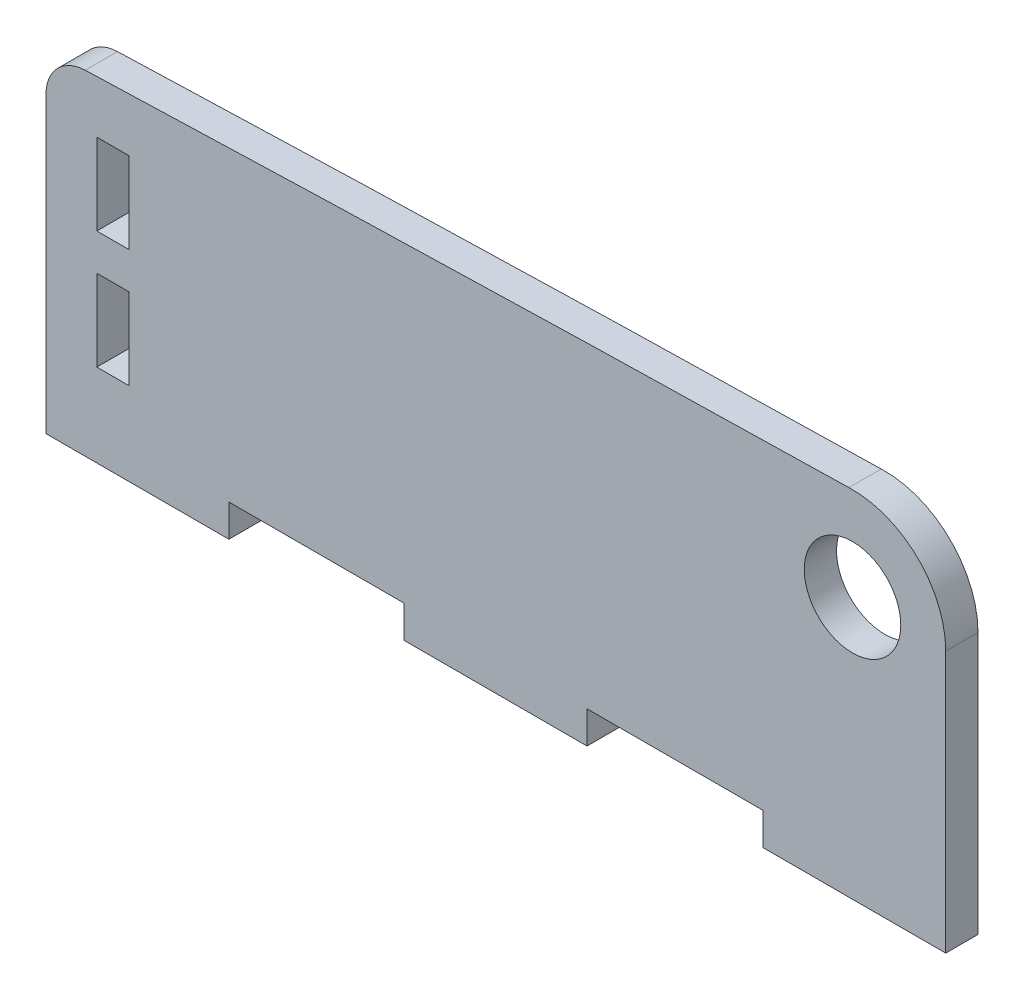
SolidWorks part; units mm, degrees
ref_plane "Front Plane" through (0, 0, 0) normal (0, 0, 1) x (1, 0, 0)
ref_plane "Top Plane" through (0, 0, 0) normal (0, 1, 0) x (1, 0, 0)
ref_plane "Right Plane" through (0, 0, 0) normal (1, 0, 0) x (0, 0, -1)
sketch "Sketch1" plane through (0, 0, 0) normal (0, 0, 1) x (1, 0, 0)
  line L1 (-26.416, -9.8) -> (26.416, -9.8)
  line L2 (-26.416, -9.8) -> (-26.416, 9.8)
  line L3 (-26.416, 9.8) -> (26.416, 9.8)
  line L4 (26.416, -9.8) -> (26.416, 9.8)
  line L5 (-26.416, -9.8) -> (26.416, 9.8) construction
  line L6 (-26.416, 9.8) -> (26.416, -9.8) construction
  line L7 (-20.15, -9.8) -> (20.15, -9.8)
  line L8 (-20.15, -9.8) -> (-20.15, 9.8)
  line L9 (-20.15, 9.8) -> (20.15, 9.8)
  line L10 (20.15, -9.8) -> (20.15, 9.8)
  line L11 (-20.15, -9.8) -> (20.15, 9.8) construction
  line L12 (-20.15, 9.8) -> (20.15, -9.8) construction
  line L13 (-26.416, 9.8) -> (26.416, 9.8)
  line L14 (-26.416, 9.8) -> (-26.416, 14.8)
  line L15 (-26.416, 14.8) -> (26.416, 14.8)
  line L16 (26.416, 9.8) -> (26.416, 14.8)
  line L17 (26.416, -9.8) -> (-26.416, -9.8)
  line L18 (26.416, -9.8) -> (26.416, -14.8)
  line L19 (26.416, -14.8) -> (-26.416, -14.8)
  line L20 (-26.416, -9.8) -> (-26.416, -14.8)
  circle A0 centre (-23.95, -4.974) radius 1.675
  circle A1 centre (-23.95, 4.974) radius 1.675
  circle A2 centre (23.95, 4.974) radius 1.675
  circle A3 centre (23.95, -4.974) radius 1.675
  point P0 (0, 0)
  point P14 (0, 0)
  dimension "D1" = 3.35
  dimension "D2" = 3.35
  dimension "D3" = 3.35
  dimension "D4" = 3.35
  dimension "D7" = 4.826
  dimension "D8" = 3.8
  dimension "D9" = 3.8
  dimension "D10" = 4.826
  dimension "D11" = 4.826
  dimension "D12" = 4.826
  dimension "D13" = 3.8
  dimension "D5" = 19.6
  dimension "D6" = 52.832
  dimension "D15" = 40.3
  dimension "D16" = 5
  dimension "D17" = 5
  dimension "3.9" = 3.8
extrude "Boss-Extrude2" add sketch "Sketch1" along normal blind 3.175 contours L1 L8 L3 L2 A1 A0 | L10 L1 L4 L3 A3 A2 | L14 L13 L16 L15 | L18 L17 L20 L19
sketch "Sketch3" plane through (0, 0, 3.175) normal (0, 0, 1) x (1, 0, 0)
  line L0 (26.416, -14.8) -> (56.416, -14.8)
  line L6 (26.416, 14.8) -> (56.416, 14.8)
  line L7 (26.416, 14.8) -> (26.416, -14.906)
  line L8 (26.416, -14.906) -> (56.416, -14.906)
  line L9 (56.416, 14.8) -> (56.416, -14.906)
  line M3 (26.416, -14.8) -> (26.416, 14.8)
  dimension "D2" = 30
extrude "Boss-Extrude3" add sketch "Sketch3" against normal up to surface (3.175 mm away) contours L9 L6 L0 M3 up to face at (0, 0, 0)
sketch "Sketch4" plane through (0, 0, 0) normal (0, 0, -1) x (-1, 0, 0)
  line L3 (-56.416, 14.8) -> (-56.416, -14.8) construction
  line L4 (-56.416, -14.8) -> (26.416, -14.8) construction
  circle A0 centre (-40.576, 7.77) radius 4.75
  dimension "D1" = 15.84
  dimension "D2" = 22.57
  dimension "D3" = 9.5
extrude "Cut-Extrude1" cut sketch "Sketch4" against normal blind 10 contours A0
sketch "Sketch22" plane through (0, 0, 0) normal (0, 0, -1) x (-1, 0, 0)
  line L0 (-52.3294, 14.8) -> (-30.0917, 14.8)
  line L1 (26.416, 14.8) -> (-56.416, 14.8) construction
  circle A0 centre (-40.576, 7.77) radius 9.175
  dimension "D1" = 18.35
extrude "Boss-Extrude14" add sketch "Sketch22" against normal up to surface (3.175 mm away) contours L0 A0
sketch "Sketch23" plane through (0, 0, 0) normal (0, 0, -1) x (-1, 0, 0)
  line L0 (-49.751, 7.77) -> (-49.751, -14.8)
  line L1 (-56.416, -14.8) -> (26.416, -14.8) construction
  circle A0 centre (-40.576, 7.77) radius 9.175
  line M4 (-46.4717, 14.8) -> (-56.416, 14.8)
  line M5 (-56.416, 14.8) -> (-56.416, -14.8)
  line M6 (-56.416, -14.8) -> (26.416, -14.8)
extrude "Cut-Extrude8" cut sketch "Sketch23" against normal blind 10 contours A0 L0 M4 M5 M6
sketch "Sketch24" plane through (0, 0, 0) normal (0, 0, -1) x (-1, 0, 0)
  line L0 (25.625, 4.974) -> (25.625, 17.1862)
  line L1 (21.4452, -14.8) -> (27.751, -14.8)
  line L2 (-49.751, -14.8) -> (26.416, -14.8) construction
  line L3 (26.416, 14.8) -> (-34.6803, 14.8) construction
  line L4 (25.625, 14.8) -> (30.625, 14.8)
  line L5 (25.625, 14.8) -> (25.625, -14.8)
  line L6 (25.625, -14.8) -> (30.625, -14.8)
  line L7 (30.625, 14.8) -> (30.625, -14.8)
  circle A0 centre (23.95, 4.974) radius 1.675 construction
  line M14 (26.416, -14.8) -> (26.416, 14.8)
  dimension "D1" = 5
extrude "Boss-Extrude15" add sketch "Sketch24" against normal up to surface (3.175 mm away) contours L7 L4 L1 L6 M14 up to face at (45.326, 7.77, 3.175)
sketch "Sketch25" plane through (0, 0, 0) normal (0, 0, -1) x (-1, 0, 0)
  line L0 (30.625, 14.8) -> (30.625, -14.8) construction
  line L1 (30.625, 9.8) -> (33.8, 9.8)
  line L2 (30.625, 9.8) -> (30.625, 1.8)
  line L3 (30.625, 1.8) -> (33.8, 1.8)
  line L4 (33.8, 9.8) -> (33.8, 1.8)
  line L5 (28.9462, -14.8) -> (31.8791, -14.8)
  line L6 (30.625, -1.8) -> (33.8, -1.8)
  line L7 (30.625, -1.8) -> (30.625, -9.8)
  line L8 (30.625, -9.8) -> (33.8, -9.8)
  line L9 (33.8, -1.8) -> (33.8, -9.8)
  line L10 (-49.751, -14.8) -> (30.625, -14.8) construction
  line L12 (30.625, 14.8) -> (38.8, 14.8)
  line L13 (30.625, 14.8) -> (30.625, -14.8)
  line L14 (30.625, -14.8) -> (38.8, -14.8)
  line L15 (38.8, 14.8) -> (38.8, -14.8)
  line M23 (30.625, -14.8) -> (30.625, 14.8)
  dimension "D1" = 3.175
  dimension "D2" = 3.175
  dimension "D3" = 8
  dimension "D4" = 8
  dimension "D5" = 5
  dimension "D6" = 0
  dimension "D7" = 8.175
  dimension "D8" = 5
extrude "Boss-Extrude16" add sketch "Sketch25" against normal up to surface (3.175 mm away) contours L15 L12 L1 L4 L3 L6 L9 L8 L5 L14 M23 up to face at (45.326, 7.77, 3.175)
sketch "Sketch26" plane through (0, 0, 0) normal (0, 0, -1) x (-1, 0, 0)
  line L0 (-34.6803, 14.8) -> (38.8, 14.8)
  arc A0 (-40.576, 16.945) -> (38.8, 14.8) centre (-135.5308, -4966.6007) cw
  arc A1 (-34.6803, 14.8) -> (-49.751, 7.77) centre (-40.576, 7.77) ccw construction
  circle A2 centre (-40.576, 7.77) radius 9.175
  arc M18 (-34.6803, 14.8) -> (-49.751, 7.77) centre (-40.576, 7.77) ccw
  line M22 (38.8, 14.8) -> (-34.6803, 14.8)
extrude "Boss-Extrude17" add sketch "Sketch26" against normal up to surface (3.175 mm away) contours A0 M18 M22 up to face at (-32.2125, 5.8, 3.175)
fillet "Fillet5" radius 4 1 edges at (-38.8, 14.8, 1.5875)
sketch "Sketch27" plane through (0, 0, 0) normal (0, 0, -1) x (-1, 0, 0)
  line L0 (-49.751, -14.8) -> (38.8, -14.8) construction
  line L1 (-44.751, -9.8) -> (-41.576, -9.8)
  line L2 (-44.751, -9.8) -> (-44.751, -1.8)
  line L3 (-44.751, -1.8) -> (-41.576, -1.8)
  line L4 (-41.576, -9.8) -> (-41.576, -1.8)
  line L5 (-49.751, 7.77) -> (-49.751, -14.8) construction
  dimension "D1" = 3.175
  dimension "D2" = 8
  dimension "D3" = 5
  dimension "D4" = 5
extrude "Cut-Extrude9" cut sketch "Sketch27" against normal blind 10
sketch "Sketch28" plane through (0, 0, 0) normal (0, 0, -1) x (-1, 0, 0)
  line L0 (-49.751, -14.8) -> (38.8, -14.8) construction
  line L1 (-49.751, -14.8) -> (-31.751, -14.8)
  line L2 (-49.751, -14.8) -> (-49.751, -17.975)
  line L3 (-49.751, -17.975) -> (-31.751, -17.975)
  line L4 (-31.751, -14.8) -> (-31.751, -17.975)
  line L5 (-14.45, -14.8) -> (3.55, -14.8)
  line L6 (-14.45, -14.8) -> (-14.45, -17.975)
  line L7 (-14.45, -17.975) -> (3.55, -17.975)
  line L8 (3.55, -14.8) -> (3.55, -17.975)
  line L9 (38.8, 10.936) -> (38.8, -14.8) construction
  line L10 (20.8, -14.8) -> (38.8, -14.8)
  line L11 (20.8, -14.8) -> (20.8, -17.975)
  line L12 (20.8, -17.975) -> (38.8, -17.975)
  line L13 (38.8, -14.8) -> (38.8, -17.975)
  dimension "D1" = 3.175
  dimension "D2" = 3.175
  dimension "D3" = 3.175
  dimension "D4" = 18
  dimension "D5" = 18
  dimension "D6" = 18
  dimension "D7" = 0
  dimension "D8" = 17.25
extrude "Boss-Extrude18" add sketch "Sketch28" against normal up to surface (3.175 mm away) contours L2 L1 L4 L3 | L6 L5 L8 L7 | L11 L10 L13 L12 up to face at (43.1635, -5.8, 3.175)
sketch "Sketch29" plane through (0, 0, 0) normal (0, 0, -1) x (-1, 0, 0)
  line L1 (-26.5134, -10.9888) -> (27.3004, -10.9888)
  line L2 (-26.5134, -10.9888) -> (-26.5134, 12.487)
  line L3 (-26.5134, 12.487) -> (27.3004, 12.487)
  line L4 (27.3004, -10.9888) -> (27.3004, 12.487)
extrude "Boss-Extrude19" add sketch "Sketch29" against normal up to surface (3.175 mm away) up to face at (43.1635, -5.8, 3.175)
sketch "Sketch30" plane through (0, 0, 0) normal (0, 0, -1) x (-1, 0, 0)
  line L1 (-45.8358, -11.1694) -> (-37.6193, -11.1694)
  line L2 (-45.8358, -11.1694) -> (-45.8358, 0)
  line L3 (-45.8358, 0) -> (-37.6193, 0)
  line L4 (-37.6193, -11.1694) -> (-37.6193, 0)
extrude "Boss-Extrude20" add sketch "Sketch30" against normal up to surface (3.175 mm away) up to face at (43.1635, -5.8, 3.175)
